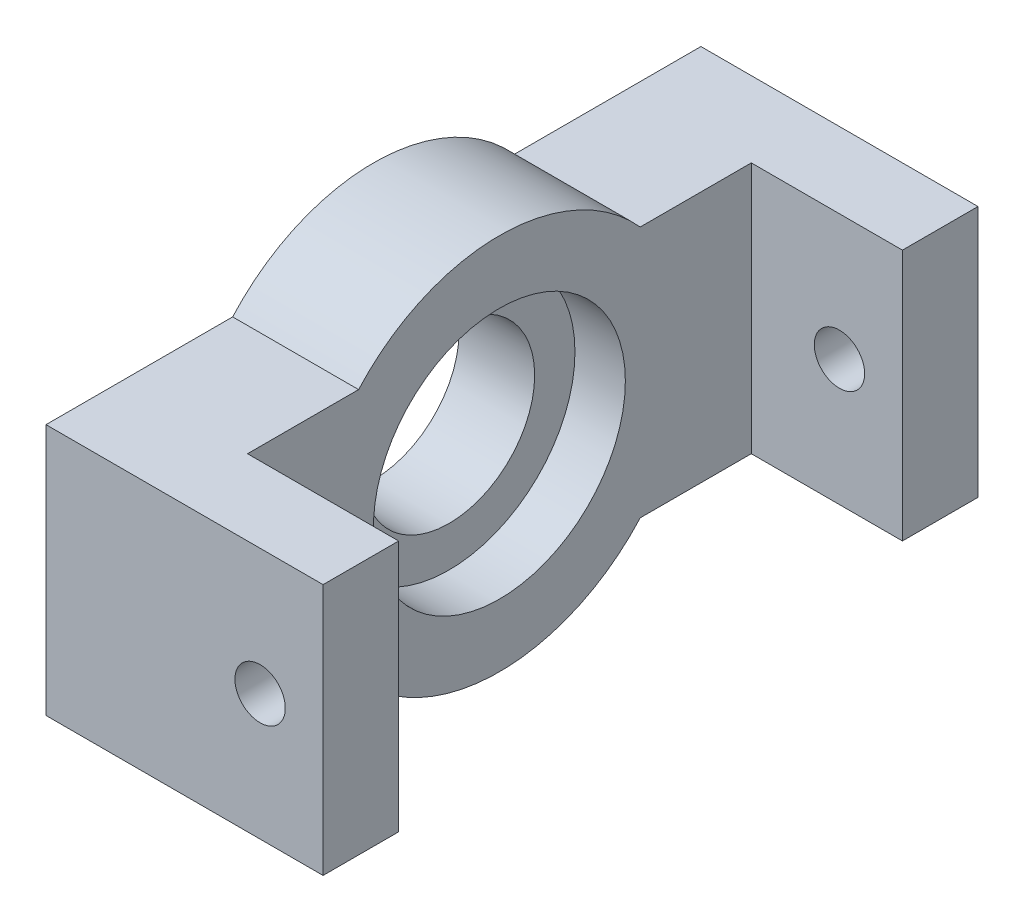
SolidWorks part; units mm, degrees
ref_plane "前视基准面" through (0, 0, 0) normal (0, 0, 1) x (1, 0, 0)
ref_plane "上视基准面" through (0, 0, 0) normal (0, 1, 0) x (1, 0, 0)
ref_plane "右视基准面" through (0, 0, 0) normal (1, 0, 0) x (0, 0, -1)
sketch "草图1" plane through (0, 0, 0) normal (1, 0, 0) x (0, 0, -1)
  circle A0 centre (0, 0) radius 7.5
  dimension "D1" = 15
extrude "凸台-拉伸1" add sketch "草图1" along normal blind 5
sketch "草图2" plane through (5, 0, 0) normal (1, 0, 0) x (0, 0, -1)
  circle A0 centre (0, 0) radius 5
extrude "切除-拉伸1" cut sketch "草图2" against normal blind 2
sketch "草图3" plane through (3, 0, 0) normal (1, 0, 0) x (0, 0, -1)
  circle A0 centre (0, 0) radius 3.4
  dimension "D1" = 6.8
extrude "切除-拉伸2" cut sketch "草图3" against normal through all
sketch "草图4" plane through (5, 0, 0) normal (1, 0, 0) x (0, 0, -1)
  line L0 (5.5902, 5) -> (5.5902, -5)
  line L1 (-13, 5) -> (-5.5902, 5)
  line L2 (-13, 5) -> (-13, -5)
  line L3 (-13, -5) -> (-5.5902, -5)
  line L4 (13, 5) -> (13, -5)
  line L5 (-5.5902, 5) -> (-5.5902, -5)
  line L6 (5.5902, 5) -> (13, 5)
  line L7 (5.5902, -5) -> (13, -5)
  circle A0 centre (0, 0) radius 7.5 construction
  circle A1 centre (0, 0) radius 7.5 construction
  dimension "D3" = 13
  dimension "D1" = 10
  dimension "D2" = 26
  dimension "D4" = 5
extrude "凸台-拉伸3" add sketch "草图4" against normal blind 5
sketch "草图5" plane through (5, 0, 0) normal (1, 0, 0) x (0, 0, -1)
  line L0 (5.5902, -5) -> (13, -5) construction
  line L1 (13, 5) -> (10, 5)
  line L2 (13, 5) -> (13, -5)
  line L3 (13, -5) -> (10, -5)
  line L4 (10, 5) -> (10, -5)
  line L5 (-13, -5) -> (-5.5902, -5) construction
  line L6 (-13, 5) -> (-10, 5)
  line L7 (-13, 5) -> (-13, -5)
  line L8 (-13, -5) -> (-10, -5)
  line L9 (-10, 5) -> (-10, -5)
  dimension "D1" = 3
  dimension "D2" = 3
extrude "凸台-拉伸4" add sketch "草图5" along normal blind 6
sketch "草图6" plane through (0, 0, -13) normal (0, 0, -1) x (-1, 0, 0)
  line L0 (-11, -5) -> (-11, 5) construction
  line L1 (0, -5) -> (-11, -5) construction
  circle A0 centre (-8.5, 0) radius 1
  dimension "D1" = 2
  dimension "D2" = 2.5
  dimension "D3" = 5
extrude "切除-拉伸3" cut sketch "草图6" against normal through all
